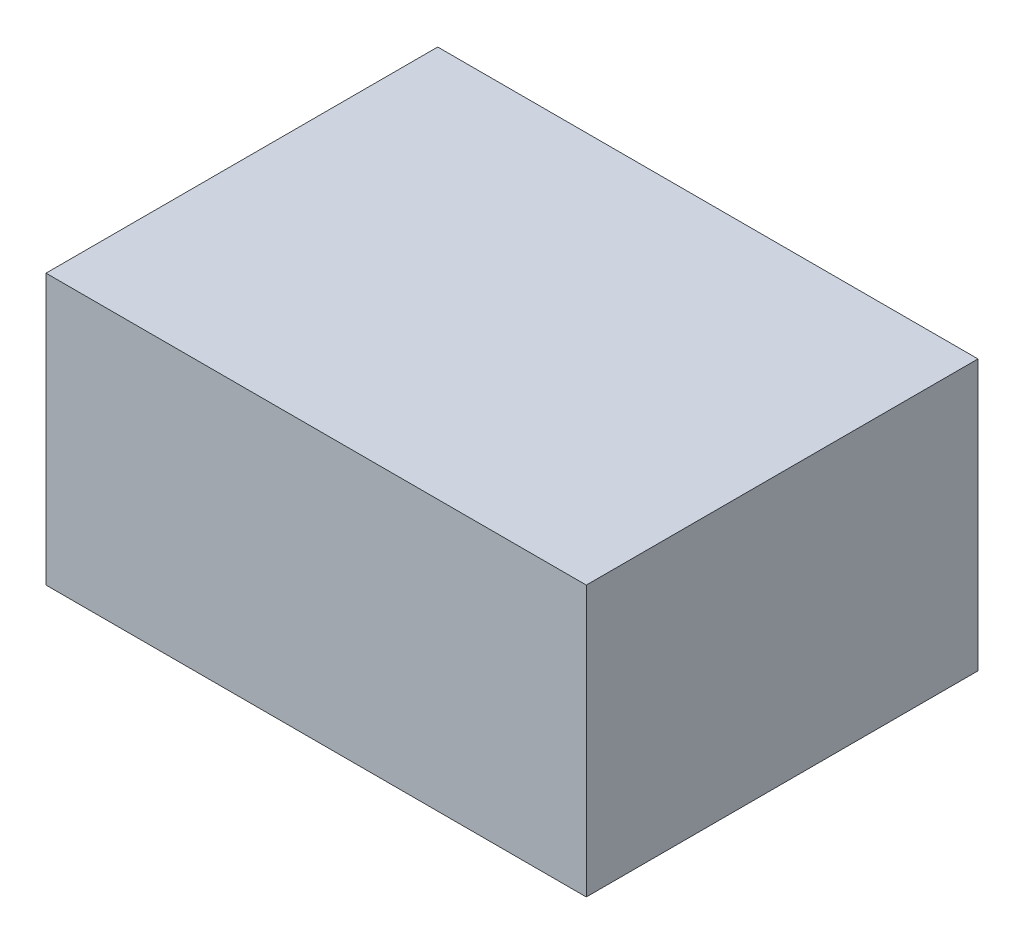
SolidWorks part; units mm, degrees
material "1060 Alloy"
ref_plane "Front Plane" through (0, 0, 0) normal (0, 0, 1) x (1, 0, 0)
ref_plane "Top Plane" through (0, 0, 0) normal (0, 1, 0) x (1, 0, 0)
ref_plane "Right Plane" through (0, 0, 0) normal (1, 0, 0) x (0, 0, -1)
sketch "Sketch1" plane through (0, 0, 0) normal (0, 0, 1) x (1, 0, 0)
  point P16 (0, 0)
sketch "Sketch6" plane through (0, 0, 0) normal (0, 1, 0) x (1, 0, 0)
  line L5 (40, 29) -> (-40, 29)
  line L6 (40, 29) -> (40, -29)
  line L11 (40, -29) -> (-40, -29)
  line L12 (-40, 29) -> (-40, -29)
  line L13 (40, 29) -> (-40, -29) construction
  line L14 (40, -29) -> (-40, 29) construction
  point P0 (0, 0)
  dimension "D1" = 58
  dimension "D2" = 80
extrude "Boss-Extrude1" add sketch "Sketch6" along normal blind 40
sketch "Sketch7" plane through (0, 0, 29) normal (0, 0, 1) x (1, 0, 0)
  line L0 (25, 40) -> (40, 40)
  line L1 (-40, 40) -> (40, 40) construction
  line L2 (40, 40) -> (40, 31.3397)
  line L3 (40, 40) -> (40, 0) construction
  line L4 (40, 31.3397) -> (25, 40)
  line L5 (-40, 19) -> (40, 19) construction
  line L7 (40, 8.6603) -> (25, 0)
  line L8 (40, 0) -> (40, 8.6603)
  line L9 (25, 0) -> (40, 0)
  line L10 (-40, 40) -> (-40, 0) construction
  line L11 (-40, 0) -> (40, 0) construction
  line L12 (-40, -34.4086) -> (-40, -10) construction
  circle A0 centre (-6, 19) radius 7.5
  circle A1 centre (10, -10) radius 50
  dimension "D6" = 15
  dimension "D9" = 100
  dimension "D1" = 15
  dimension "D2" = 30
  dimension "D3" = 30
  dimension "D4" = 15
  dimension "D5" = 19
  dimension "D7" = 31
  dimension "D8" = 24.4086
equation "\"a\"= 58mm"
equation "\"b\"= 40mm"
equation "\"c\"= 65mm"
